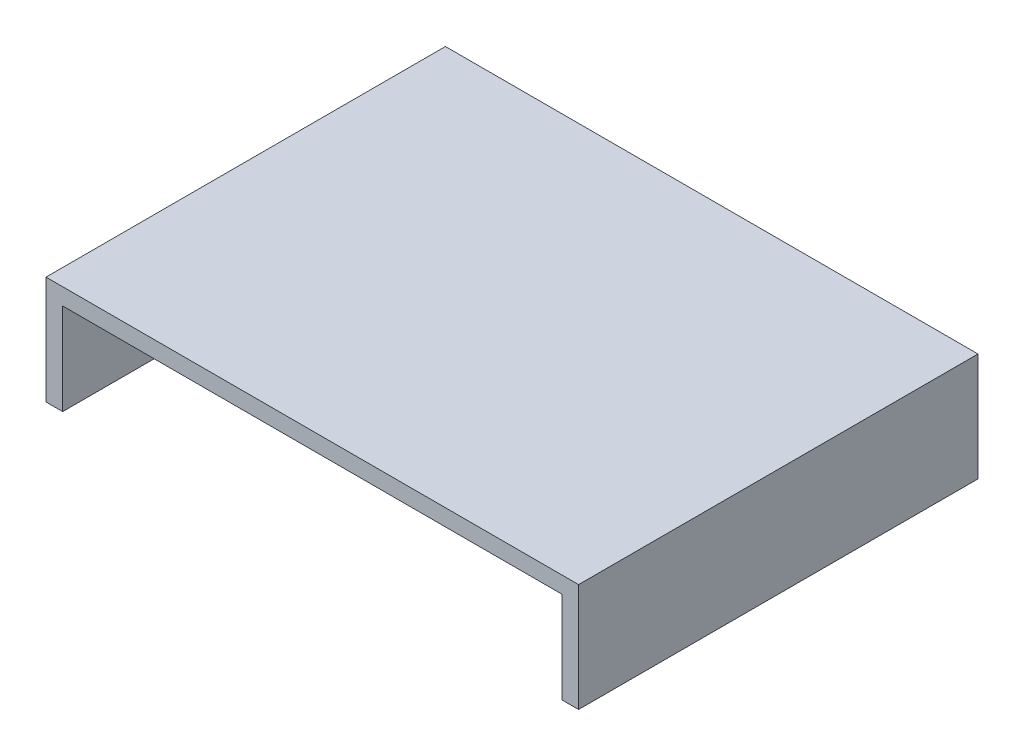
SolidWorks part; units mm, degrees
ref_plane "Front Plane" through (0, 0, 0) normal (0, 0, 1) x (1, 0, 0)
ref_plane "Top Plane" through (0, 0, 0) normal (0, 1, 0) x (1, 0, 0)
ref_plane "Right Plane" through (0, 0, 0) normal (1, 0, 0) x (0, 0, -1)
sketch "Sketch1" plane through (0, 0, 0) normal (0, 0, 1) x (1, 0, 0)
  line L0 (0, 0) -> (0, 11)
  line L1 (0, 11) -> (60, 11)
  line L2 (60, 11) -> (60, 0)
  line L3 (60, 0) -> (62, 0)
  line L4 (62, 0) -> (62, 13)
  line L5 (62, 13) -> (-2, 13)
  line L6 (-2, 13) -> (-2, 0)
  line L7 (-2, 0) -> (0, 0)
  point P9 (0, 0)
  point P10 (-1, 0)
  dimension "D1" = 2
  dimension "D2" = 2
  dimension "D3" = 64
  dimension "D4" = 2
  dimension "D5" = 13
extrude "Boss-Extrude1" add sketch "Sketch1" along normal blind 48
